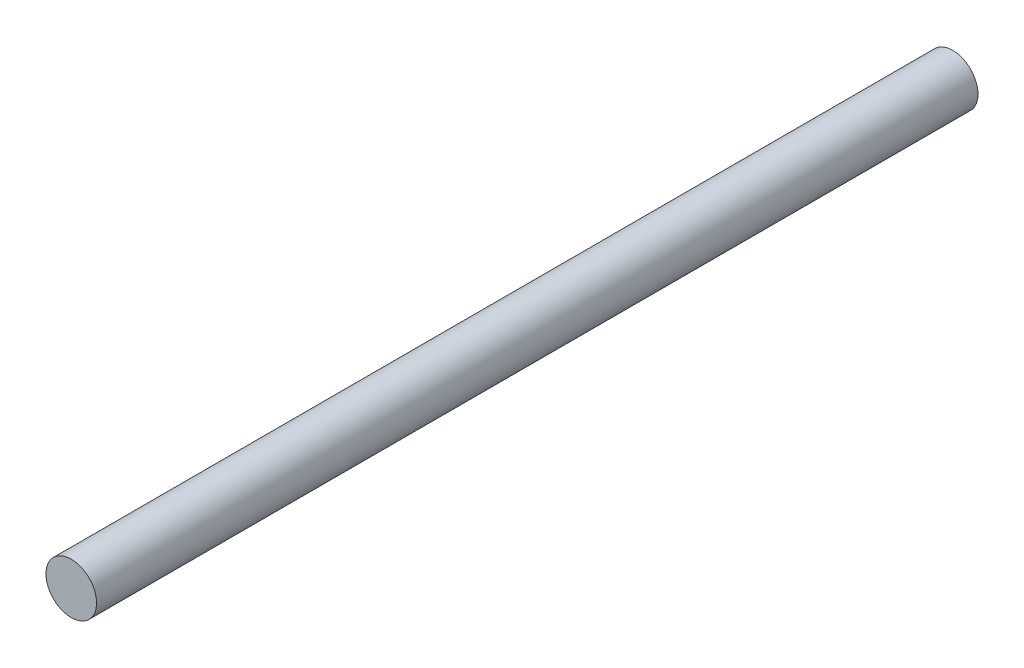
SolidWorks part; units mm, degrees
material "5052-O"
ref_plane "正面" through (0, 0, 0) normal (0, 0, 1) x (1, 0, 0)
ref_plane "平面" through (0, 0, 0) normal (0, 1, 0) x (1, 0, 0)
ref_plane "右側面" through (0, 0, 0) normal (1, 0, 0) x (0, 0, -1)
sketch "ｽｹｯﾁ1" plane through (0, 0, 0) normal (0, 0, 1) x (1, 0, 0)
  circle A0 centre (0, 0) radius 3
  dimension "D1" = 6
extrude "ﾎﾞｽ - 押し出し1" add sketch "ｽｹｯﾁ1" along normal blind 104.5
